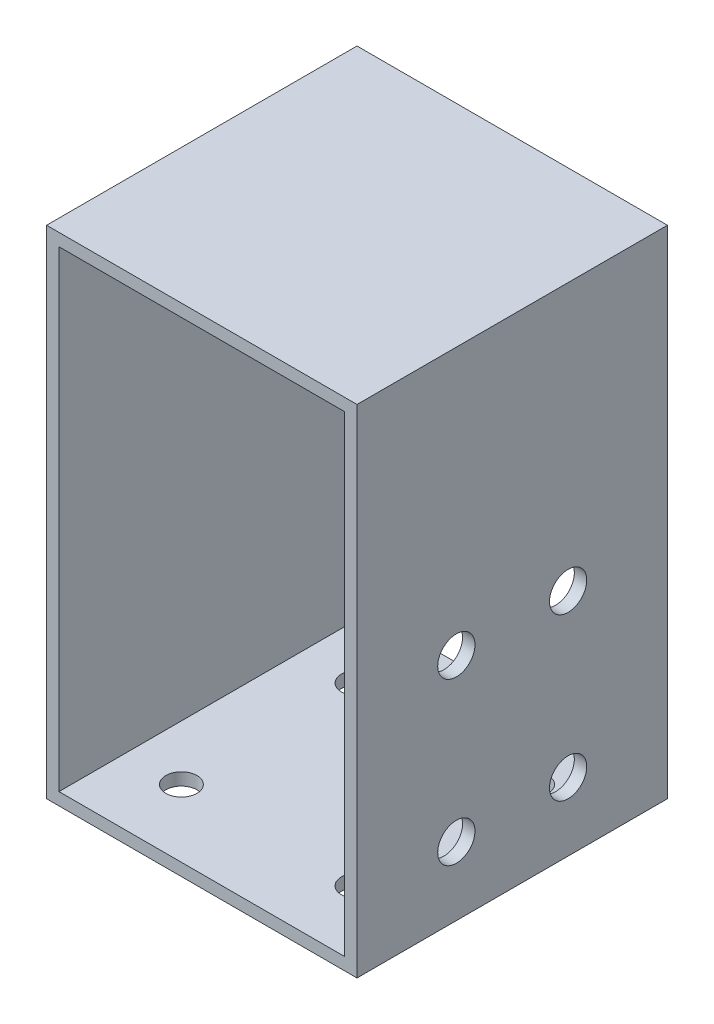
SolidWorks part; units mm, degrees
material "6063-T5"
ref_plane "前视基准面" through (0, 0, 0) normal (0, 0, 1) x (1, 0, 0)
ref_plane "上视基准面" through (0, 0, 0) normal (0, 1, 0) x (1, 0, 0)
ref_plane "右视基准面" through (0, 0, 0) normal (1, 0, 0) x (0, 0, -1)
sketch "草图1" plane through (0, 0, 0) normal (0, 0, 1) x (1, 0, 0)
  line L0 (-11.5, -19) -> (-11.5, 19)
  line L1 (-12.5, -20) -> (12.5, -20)
  line L2 (-12.5, -20) -> (-12.5, 20)
  line L3 (-12.5, 20) -> (12.5, 20)
  line L4 (12.5, -20) -> (12.5, 20)
  line L5 (-12.5, -20) -> (12.5, 20) construction
  line L6 (-12.5, 20) -> (12.5, -20) construction
  line L7 (-11.5, 19) -> (11.5, 19)
  line L8 (11.5, -19) -> (11.5, 19)
  line L9 (-11.5, -19) -> (11.5, -19)
  point P0 (0, 0)
  dimension "D1" = 25
  dimension "D2" = 40
  dimension "D3" = 1
extrude "凸台-拉伸1" add sketch "草图1" along normal mid plane 25
sketch "草图2" plane through (0, -19, 0) normal (0, 1, 0) x (1, 0, 0)
  circle A0 centre (7.0711, -7.0711) radius 1.25 construction
  circle A1 centre (7.0711, 7.0711) radius 1.25 construction
  circle A2 centre (-7.0711, 7.0711) radius 1.25 construction
  circle A3 centre (-7.0711, -7.0711) radius 1.25 construction
  circle A4 centre (7.0711, -7.0711) radius 1.25
  circle A5 centre (7.0711, 7.0711) radius 1.25
  circle A6 centre (-7.0711, 7.0711) radius 1.25
  circle A7 centre (-7.0711, -7.0711) radius 1.25
extrude "切除-拉伸1" cut sketch "草图2" against normal blind 10
sketch "草图3" plane through (11.5, 0, 0) normal (-1, 0, 0) x (0, 0, 1)
  circle A0 centre (-4.5, -14.5) radius 1.25 construction
  circle A1 centre (4.5, -14.5) radius 1.25 construction
  circle A2 centre (4.5, -1.5) radius 1.25 construction
  circle A3 centre (-4.5, -1.5) radius 1.25 construction
  circle A4 centre (-4.5, -14.5) radius 1.25 construction
  circle A5 centre (4.5, -14.5) radius 1.25 construction
  circle A6 centre (4.5, -1.5) radius 1.25 construction
  circle A7 centre (-4.5, -1.5) radius 1.25 construction
  circle A8 centre (4.5, -14.5) radius 1.5
  circle A9 centre (-4.5, -14.5) radius 1.5
  circle A10 centre (-4.5, -1.5) radius 1.5
  circle A11 centre (4.5, -1.5) radius 1.5
  dimension "D1" = 3
extrude "切除-拉伸2" cut sketch "草图3" against normal blind 10
